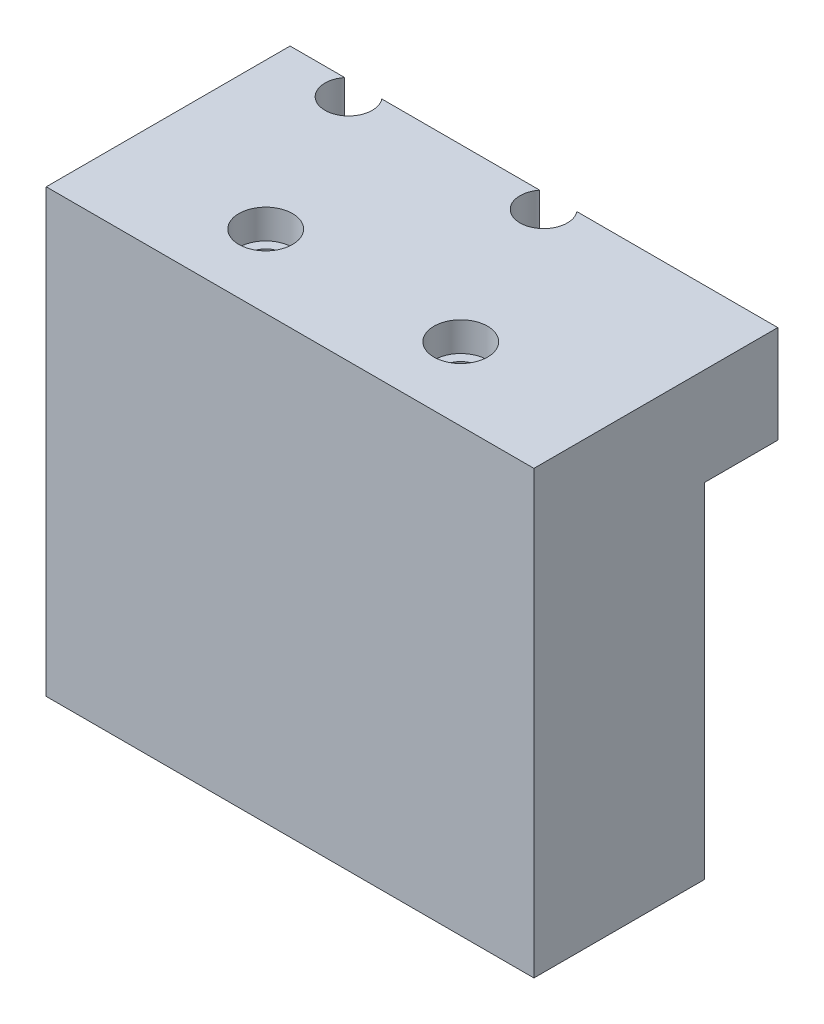
SolidWorks part; units mm, degrees
material "S45C表面镀硬铬"
ref_plane "前基準面" through (0, 0, 0) normal (0, 0, 1) x (1, 0, 0)
ref_plane "上基準面" through (0, 0, 0) normal (0, 1, 0) x (1, 0, 0)
ref_plane "右基準面" through (0, 0, 0) normal (1, 0, 0) x (0, 0, -1)
sketch "草图1" plane through (0, 0, 0) normal (0, 0, 1) x (1, 0, 0)
  line L1 (0, 0) -> (100, 0)
  line L2 (0, 0) -> (0, 90.5)
  line L3 (0, 90.5) -> (100, 90.5)
  line L4 (100, 0) -> (100, 90.5)
  dimension "D1" = 100
  dimension "D2" = 90.5
extrude "凸台-拉伸1" add sketch "草图1" along normal blind 50
sketch "草图2" plane through (0, 0, 0) normal (-1, 0, 0) x (0, 0, 1)
  line L0 (50, 90.5) -> (0, 90.5) construction
  line L1 (0, 0) -> (15, 0)
  line L2 (0, 0) -> (0, 70.5)
  line L3 (0, 70.5) -> (15, 70.5)
  line L4 (15, 0) -> (15, 70.5)
  dimension "D1" = 20
  dimension "D2" = 15
extrude "切除-拉伸1" cut sketch "草图2" against normal through all
sketch "草图4" plane through (0, 90.5, 0) normal (0, 1, 0) x (1, 0, 0)
  line L0 (0, -50) -> (0, 0) construction
  line L1 (100, 0) -> (0, 0) construction
  circle A0 centre (15, -3) radius 4.85
  circle A1 centre (55, -3) radius 4.85
  dimension "D1" = 9.7
  dimension "D2" = 15
  dimension "D3" = 40
  dimension "D4" = 3
extrude "切除-拉伸3" cut sketch "草图4" against normal through all
hole_wizard "M6 六角凹头螺钉的柱形沉头孔1" positions "草图8" profile "草图7" counterbore size "M6" standard "ISO" end condition through all
sketch "草图8" plane through (0, 90.5, 0) normal (0, 1, 0) x (-1, 0, 0)
  line L0 (-50, 50) -> (-50, 5.5198) construction
  line L1 (-100, 50) -> (0, 50) construction
  point P0 (-30, 35)
  point P1 (-70, 35)
  dimension "D1" = 40
  dimension "D2" = 15
sketch "草图7" plane through (30, 90.5, 35) normal (1, 0, 0) x (0, 0, 1)
  line L0 (0, 0) -> (0, 90.5)
  line L1 (0, 90.5) -> (3.5, 90.5)
  line L3 (3.5, 90.5) -> (3.5, 6)
  line L4 (3.5, 6) -> (5.5, 6)
  line L5 (5.5, 6) -> (5.5, 0)
  line L7 (5.5, 0) -> (0, 0)
  line L11 (0, -6.35) -> (0, 107.95) construction
  dimension "通孔孔直径" = 7
  dimension "通孔孔深度" = 90.5
  dimension "柱形沉头孔直径" = 11
  dimension "柱形沉头孔深度" = 6
hole_wizard "M3 螺纹孔1" positions "草图10" profile "草图9" tap size "M3" standard "ISO"
sketch "草图10" plane through (0, 0, 0) normal (-1, 0, 0) x (0, 0, 1)
  line L0 (15, 0) -> (15, 70.5) construction
  line L1 (50, 90.5) -> (0, 90.5) construction
  point P0 (39, 65.5)
  point P1 (19.5, 65.5)
  dimension "D1" = 4.5
  dimension "D2" = 19.5
  dimension "D3" = 25
sketch "草图9" plane through (0, 65.5, 39) normal (0, 1, 0) x (0, 0, 1)
  line L0 (0, 0) -> (0, 8.2511)
  line L1 (0, 8.2511) -> (1.25, 7.5)
  line L2 (1.25, 7.5) -> (1.25, 0)
  line L5 (1.25, 0) -> (0, 0)
  line L10 (0, 8.2511) -> (-1.25, 7.5) construction
  line L11 (0, -6.35) -> (0, 107.95) construction
  dimension "螺纹孔钻头直径" = 2.5
  dimension "螺纹孔钻头深度" = 7.5
  dimension "导头角度" = 118
cosmetic thread "孔螺蚊线1" parameters "D1"=6, "D2"=3
cosmetic thread "孔螺蚊线2" parameters "D1"=6, "D2"=3
